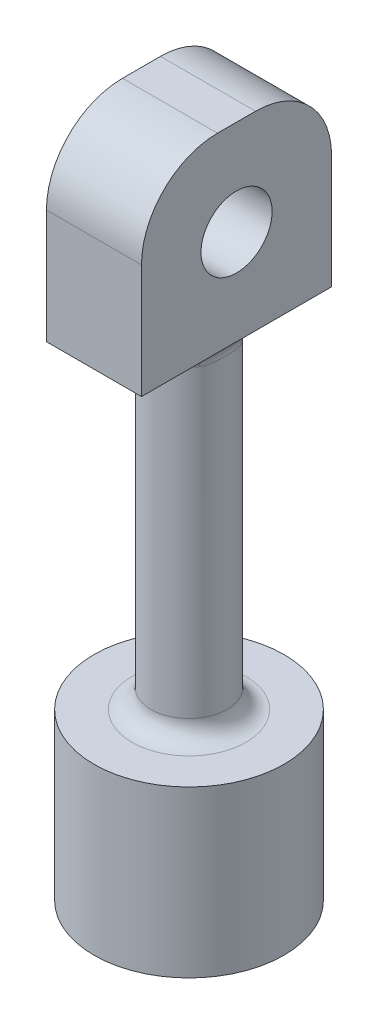
SolidWorks part; units mm, degrees
ref_plane "Front Plane" through (0, 0, 0) normal (0, 0, 1) x (1, 0, 0)
ref_plane "Top Plane" through (0, 0, 0) normal (0, 1, 0) x (1, 0, 0)
ref_plane "Right Plane" through (0, 0, 0) normal (1, 0, 0) x (0, 0, -1)
sketch "Sketch1" plane through (0, 0, 0) normal (0, 1, 0) x (1, 0, 0)
  circle A0 centre (0, 0) radius 0.25
  dimension "D1" = 0.5
extrude "Boss-Extrude1" add sketch "Sketch1" along normal blind 0.435
sketch "Sketch2" plane through (0, 0.435, 0) normal (0, 1, 0) x (1, 0, 0)
  circle A0 centre (0, 0) radius 0.1
  dimension "D1" = 0.2
extrude "Boss-Extrude2" add sketch "Sketch2" along normal blind 0.9
sketch "Sketch3" plane through (0, 1.335, 0) normal (0, 1, 0) x (1, 0, 0)
  line L5 (-0.125, 0.25) -> (0.125, 0.25)
  line L6 (-0.125, 0.25) -> (-0.125, -0.25)
  line L11 (-0.125, -0.25) -> (0.125, -0.25)
  line L12 (0.125, 0.25) -> (0.125, -0.25)
  line L13 (-0.125, 0.25) -> (0.125, -0.25) construction
  line L14 (-0.125, -0.25) -> (0.125, 0.25) construction
  point P0 (0, 0)
  point P1 (0, 0)
  point P10 (0.0719, 0)
  dimension "D1" = 0.25
  dimension "D2" = 0.5
extrude "Boss-Extrude3" add sketch "Sketch3" along normal blind 0.5
fillet "Fillet2" radius 0.2 2 edges at (0, 1.835, -0.25) (0, 1.835, 0.25)
sketch "Sketch4" plane through (0.125, 0, 0) normal (1, 0, 0) x (0, 0, -1)
  line L0 (-0.25, 1.635) -> (-0.25, 1.335) construction
  line L5 (-0.25, 1.335) -> (0.25, 1.335) construction
  circle A0 centre (0, 1.585) radius 0.0935
  point P6 (0.0108, 1.335)
  point P7 (0.0079, 1.335)
  dimension "D3" = 0.187
  dimension "D1" = 0.25
  dimension "D2" = 0.25
extrude "Cut-Extrude1" cut sketch "Sketch4" against normal blind 0.25
fillet "Fillet3" radius 0.05 2 edges at (0, 0.435, 0.1) (0, 1.335, 0.1)
